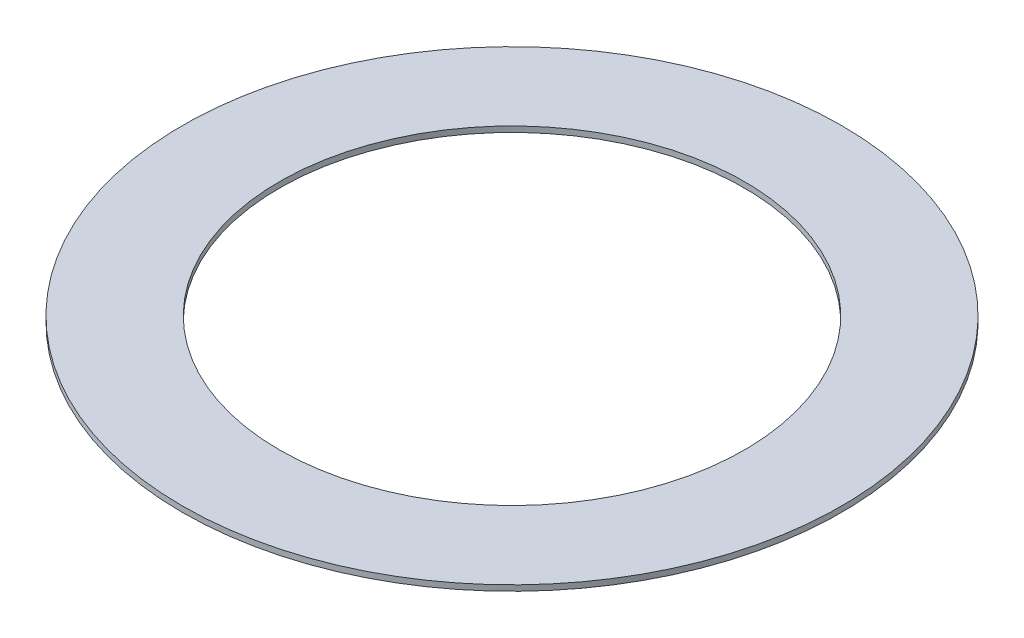
SolidWorks part; units mm, degrees
ref_plane "Front Plane" through (0, 0, 0) normal (0, 0, 1) x (1, 0, 0)
ref_plane "Top Plane" through (0, 0, 0) normal (0, 1, 0) x (1, 0, 0)
ref_plane "Right Plane" through (0, 0, 0) normal (1, 0, 0) x (0, 0, -1)
sketch "Sketch1" plane through (0, 0, 0) normal (0, 1, 0) x (1, 0, 0)
  circle A1 centre (0, 0) radius 124.092
  circle A2 centre (0, 0) radius 175.9208
extrude "Boss-Extrude1" add sketch "Sketch1" along normal blind 3
